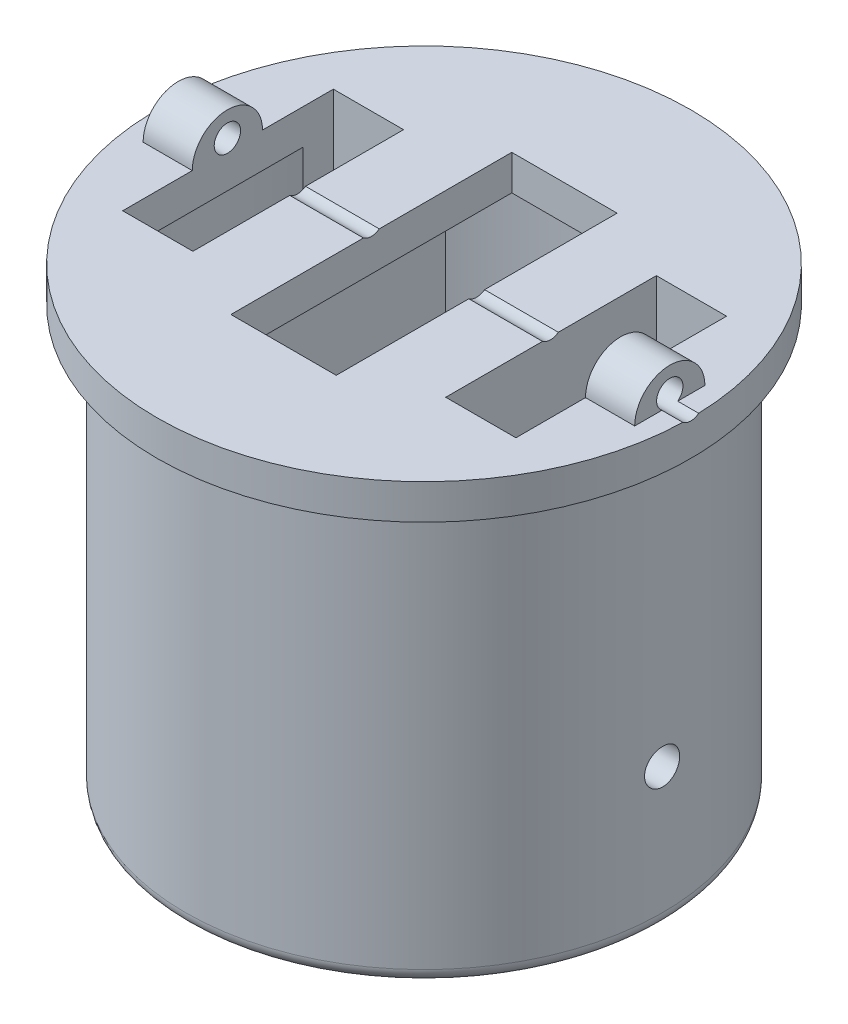
SolidWorks part; units mm, degrees
ref_plane "Front Plane" through (0, 0, 0) normal (0, 0, 1) x (1, 0, 0)
ref_plane "Top Plane" through (0, 0, 0) normal (0, 1, 0) x (1, 0, 0)
ref_plane "Right Plane" through (0, 0, 0) normal (1, 0, 0) x (0, 0, -1)
sketch "Sketch1" plane through (0, 0, 0) normal (0, 1, 0) x (1, 0, 0)
  circle A0 centre (0, 0) radius 43.18
  circle A2 centre (0, 0) radius 38.1
  dimension "D1" = 5.08
extrude "Boss-Extrude1" add sketch "Sketch1" along normal blind 76.2
sketch "Sketch4" plane through (0, 76.2, 0) normal (0, 1, 0) x (1, 0, 0)
  circle A0 centre (0, 0) radius 48.26
extrude "Boss-Extrude2" add sketch "Sketch4" along normal blind 6.35
sketch "Sketch5" plane through (0, 82.55, 0) normal (0, 1, 0) x (1, 0, 0)
  line L0 (-9.525, -25.4) -> (-9.525, 25.4)
  line L1 (-9.525, -25.4) -> (9.525, -25.4)
  line L2 (-9.525, 25.4) -> (9.525, 25.4)
  line L3 (9.525, -25.4) -> (9.525, 25.4)
  line L4 (-9.525, -25.4) -> (9.525, 25.4) construction
  line L5 (-9.525, 25.4) -> (9.525, -25.4) construction
  point P1 (0, 0)
  dimension "D1" = 50.8
  dimension "D2" = 19.05
extrude "Cut-Extrude2" cut sketch "Sketch5" against normal blind 6.35
ref_plane "Plane1" through (35.56, 0, 0) normal (1, 0, 0) x (0, 0, -1)
sketch "Sketch6" plane through (35.56, 0, 0) normal (1, 0, 0) x (0, 0, -1)
  line L0 (48.26, 82.55) -> (-48.26, 82.55) construction
  line L1 (-25.4, 82.55) -> (25.4, 82.55) construction
  line L2 (-6.35, 82.55) -> (6.35, 82.55)
  arc A0 (6.35, 82.55) -> (-6.35, 82.55) centre (0, 82.55) ccw
extrude "Boss-Extrude3" add sketch "Sketch6" along normal blind 8.89
sketch "Sketch7" plane through (35.56, 0, 0) normal (-1, 0, 0) x (0, 0, 1)
  line L2 (6.35, 82.55) -> (-6.35, 82.55) construction
  circle A1 centre (0, 84.455) radius 2.3812
  dimension "D1" = 1.905
  dimension "D2" = 4.7625
extrude "Cut-Extrude3" cut sketch "Sketch7" against normal blind 12.7 and the other way blind 86.36
mirror "Mirror1" about plane through (0, 0, 0) normal (1, 0, 0) of "Cut-Extrude3", "Boss-Extrude3"
sketch "Sketch8" plane through (0, 0, 0) normal (1, 0, 0) x (0, 0, -1)
  circle A0 centre (0, 25.4) radius 3.175
  dimension "D1" = 25.4
extrude "Cut-Extrude4" cut sketch "Sketch8" against normal blind 48.26 and the other way blind 48.26
fillet "Fillet2" radius 2.54 1 edges at (0, 0, 43.18)
sketch "Sketch9" plane through (-35.56, 0, 0) normal (1, 0, 0) x (0, 0, -1)
  point P4 (0, 88.9)
sketch "Sketch11" plane through (0, 82.55, 0) normal (0, 1, 0) x (1, 0, 0)
  line L0 (35.56, -18.9384) -> (35.56, 19.1616)
  line L1 (35.56, -6.35) -> (35.56, -1.4287) construction
  line L2 (35.56, 19.1616) -> (22.86, 19.1616)
  line L3 (22.86, 19.1616) -> (22.86, -18.9384)
  line L4 (22.86, -18.9384) -> (35.56, -18.9384)
  line L5 (0, 0) -> (0, 14.255) construction
  line L6 (-22.86, 19.1616) -> (-22.86, -18.9384)
  line L7 (-35.56, 19.1616) -> (-22.86, 19.1616)
  line L8 (-35.56, -18.9384) -> (-35.56, 19.1616)
  line L9 (-22.86, -18.9384) -> (-35.56, -18.9384)
  point P3 (35.56, 0.1116)
  dimension "D1" = 38.1
  dimension "D2" = 12.7
extrude "Cut-Extrude5" cut sketch "Sketch11" against normal blind 69.85
sketch "Sketch12" plane through (0, 76.2, 0) normal (0, -1, 0) x (1, 0, 0)
  line L0 (-19.05, 22.7484) -> (-31.75, 22.7484)
  line L1 (-19.05, 22.7484) -> (-19.05, -22.9716)
  line L2 (-19.05, -22.9716) -> (-31.75, -22.9716)
  line L3 (-33.0598, 18.9384) -> (-22.86, 18.9384) construction
  line L4 (-22.86, -19.1616) -> (-32.9309, -19.1616) construction
  line L5 (-22.86, 18.9384) -> (-22.86, -19.1616) construction
  line L6 (-31.75, 22.7484) -> (-33.0598, 18.9384)
  line L7 (-31.75, -22.9716) -> (-32.9309, -19.1616)
  line L8 (-33.0598, 18.9384) -> (-22.86, 18.9384)
  line L9 (-22.86, 18.9384) -> (-22.86, -19.1616)
  line L10 (-22.86, -19.1616) -> (-32.9309, -19.1616)
  line L11 (0, 0) -> (0, 12.92) construction
  line L12 (22.86, 18.9384) -> (22.86, -19.1616)
  line L13 (33.0598, 18.9384) -> (22.86, 18.9384)
  line L14 (31.75, 22.7484) -> (33.0598, 18.9384)
  line L15 (19.05, 22.7484) -> (31.75, 22.7484)
  line L16 (19.05, 22.7484) -> (19.05, -22.9716)
  line L17 (19.05, -22.9716) -> (31.75, -22.9716)
  line L18 (31.75, -22.9716) -> (32.9309, -19.1616)
  line L19 (22.86, -19.1616) -> (32.9309, -19.1616)
  dimension "D1" = 3.81
  dimension "D2" = 3.81
  dimension "D3" = 3.81
  dimension "D4" = 12.7
  dimension "D5" = 12.7
extrude "Boss-Extrude4" add sketch "Sketch12" along normal blind 44.45
